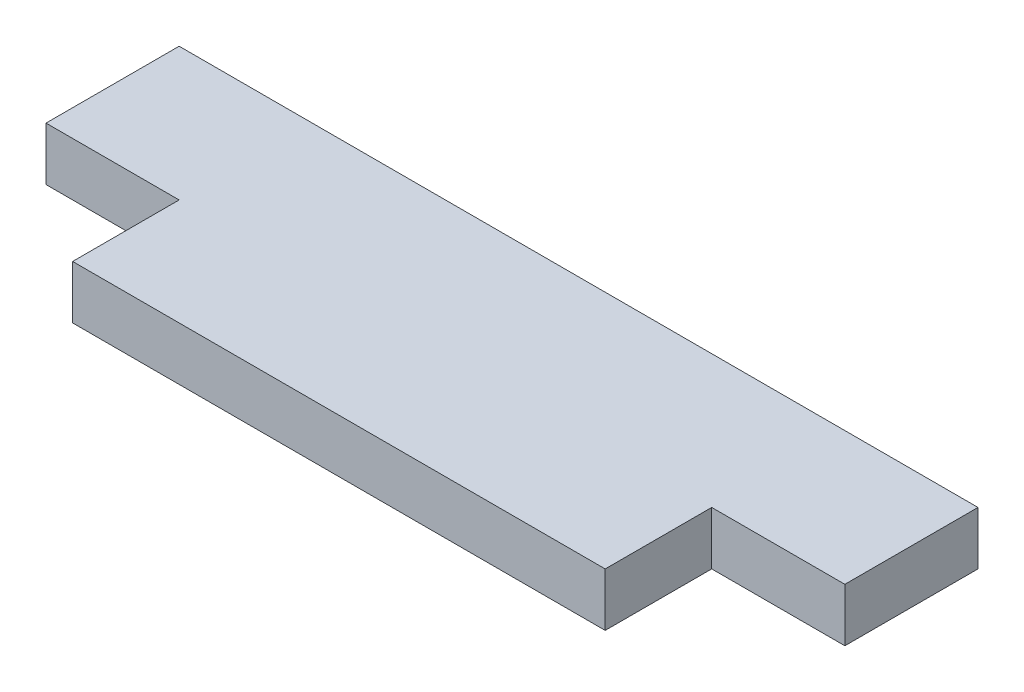
SolidWorks part; units mm, degrees
ref_plane "Front Plane" through (0, 0, 0) normal (0, 0, 1) x (1, 0, 0)
ref_plane "Top Plane" through (0, 0, 0) normal (0, 1, 0) x (1, 0, 0)
ref_plane "Right Plane" through (0, 0, 0) normal (1, 0, 0) x (0, 0, -1)
sketch "Sketch1" plane through (0, 0, 0) normal (0, 0, 1) x (1, 0, 0)
  line L1 (-10, 1) -> (10, 1)
  line L2 (-10, 1) -> (-10, -1)
  line L3 (-10, -1) -> (10, -1)
  line L4 (10, 1) -> (10, -1)
  dimension "D1" = 20
  dimension "D2" = 2
  dimension "D3" = 1
  dimension "D4" = 10
extrude "Boss-Extrude1" add sketch "Sketch1" along normal blind 4
sketch "Sketch2" plane through (0, 0, 0) normal (0, 0, -1) x (-1, 0, 0)
  line L0 (10, -1) -> (-10, -1) construction
  line L1 (15, 1) -> (-15, 1)
  line L2 (15, 1) -> (15, -1)
  line L3 (15, -1) -> (-15, -1)
  line L4 (-15, 1) -> (-15, -1)
  line L5 (-10, 1) -> (10, 1) construction
  line L6 (-10, -1) -> (-10, 1) construction
  line L7 (10, 1) -> (10, -1) construction
  dimension "D1" = 5
  dimension "D2" = 5
extrude "Boss-Extrude2" add sketch "Sketch2" along normal blind 5
